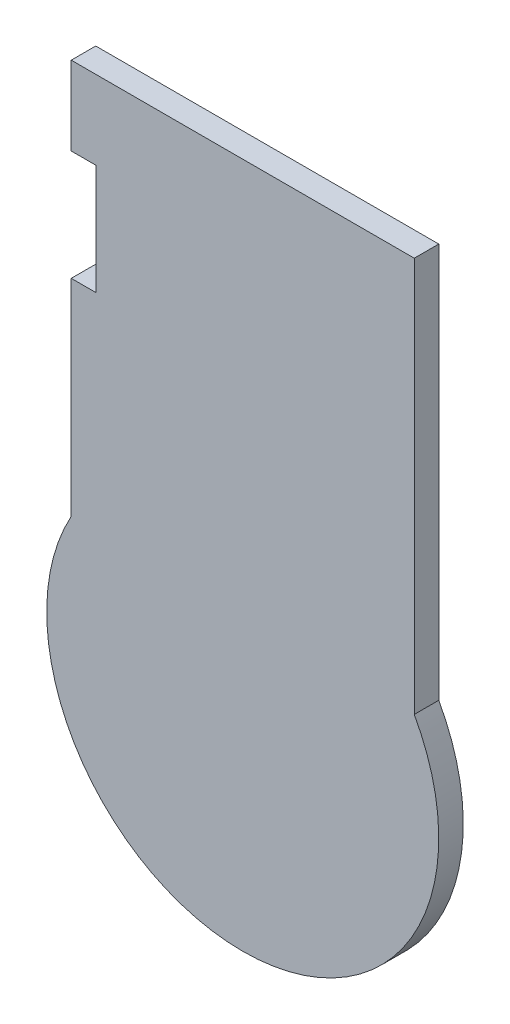
SolidWorks part; units mm, degrees
material "ﾁｰｸ材"
ref_plane "正面" through (0, 0, 0) normal (0, 0, 1) x (1, 0, 0)
ref_plane "平面" through (0, 0, 0) normal (0, 1, 0) x (1, 0, 0)
ref_plane "右側面" through (0, 0, 0) normal (1, 0, 0) x (0, 0, -1)
sketch "ｽｹｯﾁ1" plane through (0, 0, 0) normal (0, 0, 1) x (1, 0, 0)
  line L0 (35, 100) -> (-35, 100)
  line L1 (-35, 100) -> (-35, 19.3649)
  line L2 (35, 100) -> (35, 19.3649)
  arc A0 (-35, 19.3649) -> (35, 19.3649) centre (0, 0) ccw
  point P7 (0, 100)
  point P8 (-32.1537, 23.7937)
  dimension "D1" = 80
  dimension "D2" = 100
  dimension "D3" = 70
extrude "ﾎﾞｽ - 押し出し1" add sketch "ｽｹｯﾁ1" along normal blind 5
sketch "ｽｹｯﾁ2" plane through (0, 0, 5) normal (0, 0, 1) x (1, 0, 0)
  line L1 (-29.9, 61.4398) -> (-42.1, 61.4398)
  line L2 (-29.9, 61.4398) -> (-29.9, 83.9398)
  line L3 (-29.9, 83.9398) -> (-42.1, 83.9398)
  line L4 (-42.1, 61.4398) -> (-42.1, 83.9398)
  line L5 (-29.9, 61.4398) -> (-42.1, 83.9398) construction
  line L6 (-29.9, 83.9398) -> (-42.1, 61.4398) construction
  point P0 (-36, 72.6898)
  dimension "D1" = 12.2
  dimension "D2" = 22.5
  dimension "D3" = 36
extrude "ｶｯﾄ - 押し出し1" cut sketch "ｽｹｯﾁ2" against normal through all
